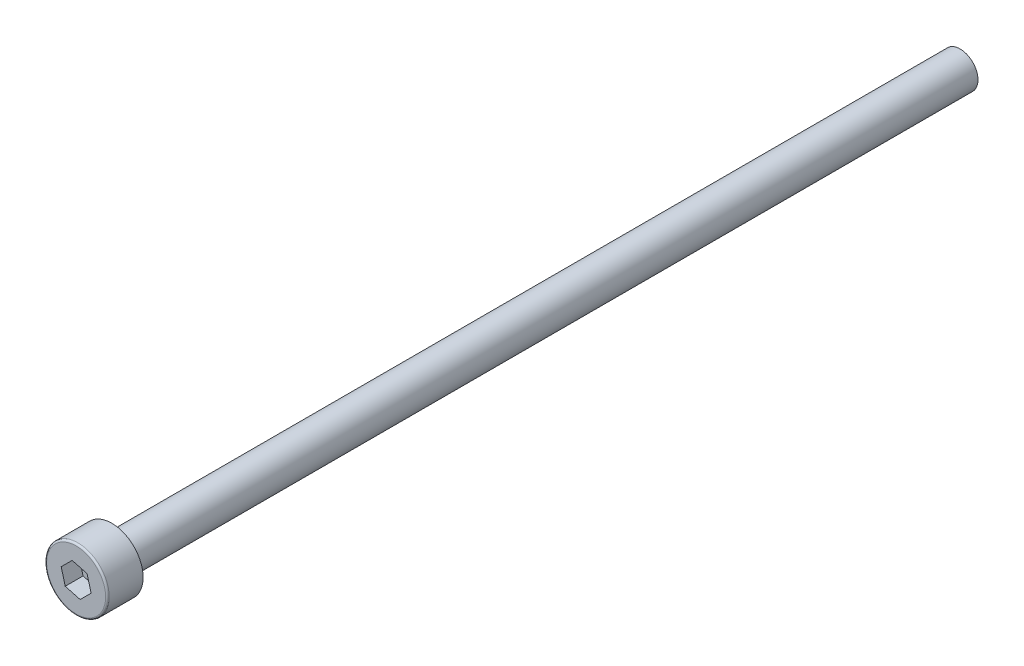
SolidWorks part; units mm, degrees
ref_plane "前视基准面" through (0, 0, 0) normal (0, 0, 1) x (1, 0, 0)
ref_plane "上视基准面" through (0, 0, 0) normal (0, 1, 0) x (1, 0, 0)
ref_plane "右视基准面" through (0, 0, 0) normal (1, 0, 0) x (0, 0, -1)
sketch "草图1" plane through (0, 0, 0) normal (0, 0, 1) x (1, 0, 0)
  circle A0 centre (0, 0) radius 3.5
  dimension "D1" = 7
extrude "凸台-拉伸1" add sketch "草图1" along normal blind 4
sketch "草图2" plane through (0, 0, 4) normal (0, 0, 1) x (1, 0, 0)
  line L1 (-1.2247, -1.2247) -> (0.4483, -1.673)
  line L2 (0.4483, -1.673) -> (1.673, -0.4483)
  line L3 (1.673, -0.4483) -> (1.2247, 1.2247)
  line L4 (1.2247, 1.2247) -> (-0.4483, 1.673)
  line L5 (-0.4483, 1.673) -> (-1.673, 0.4483)
  line L6 (-1.673, 0.4483) -> (-1.2247, -1.2247)
  circle A0 centre (0, 0) radius 1.5 construction
  dimension "D1" = 3
extrude "切除-拉伸1" cut sketch "草图2" against normal blind 2
sketch "草图3" plane through (0, 0, 0) normal (0, 0, -1) x (-1, 0, 0)
  circle A0 centre (0, 0) radius 2
  dimension "D1" = 4
extrude "凸台-拉伸2" add sketch "草图3" along normal blind 95
fillet "圆角1" radius 0.2 1 edges at (3.5, 0, 4)
